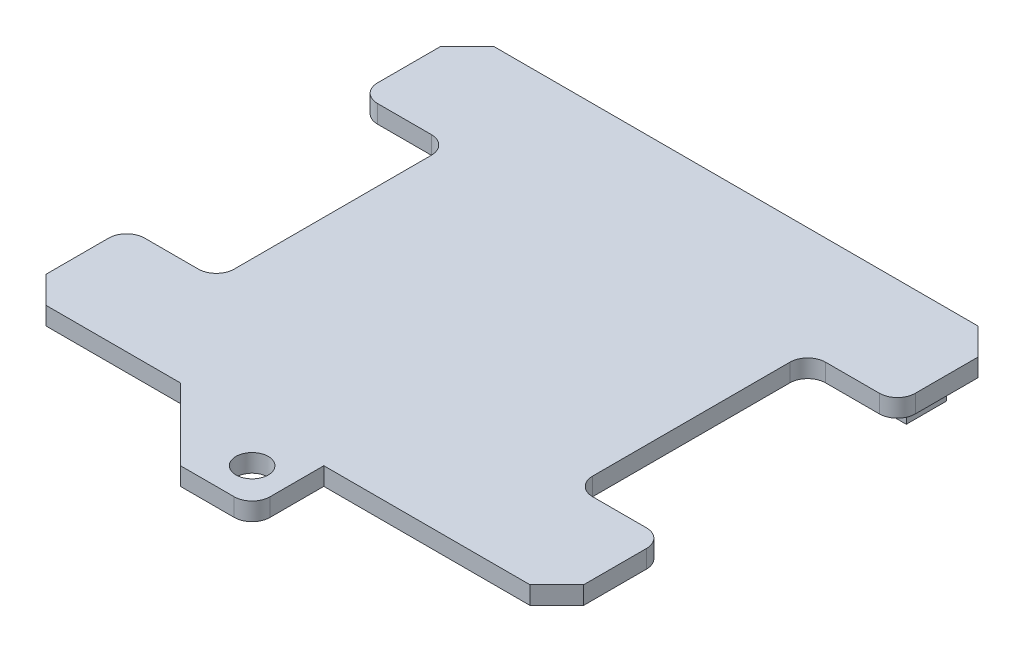
SolidWorks part; units mm, degrees
ref_plane "Front Plane" through (0, 0, 0) normal (0, 0, 1) x (1, 0, 0)
ref_plane "Top Plane" through (0, 0, 0) normal (0, 1, 0) x (1, 0, 0)
ref_plane "Right Plane" through (0, 0, 0) normal (1, 0, 0) x (0, 0, -1)
sketch "Sketch1" plane through (0, 0, 0) normal (0, 1, 0) x (1, 0, 0)
  line L1 (0, 0) -> (60, 0)
  line L2 (0, 0) -> (0, 50)
  line L3 (0, 50) -> (60, 50)
  line L4 (60, 0) -> (60, 50)
  dimension "D1" = 50
  dimension "D2" = 60
extrude "Boss-Extrude1" add sketch "Sketch1" along normal blind 2
chamfer "Chamfer1" distance 3 angle 45 4 edges at (0, 1, -50) (0, 1, 0) (60, 1, -50) (60, 1, 0)
sketch "Sketch2" plane through (0, 0, 0) normal (0, -1, 0) x (1, 0, 0)
  line L0 (2.5, -4.0355) -> (2.5, -45.9645)
  line L1 (2.5, -45.9645) -> (4.0355, -47.5)
  line L2 (4.0355, -47.5) -> (55.9645, -47.5)
  line L3 (55.9645, -47.5) -> (57.5, -45.9645)
  line L4 (57.5, -45.9645) -> (57.5, -4.0355)
  line L5 (57.5, -4.0355) -> (55.9645, -2.5)
  line L6 (55.9645, -2.5) -> (4.0355, -2.5)
  line L7 (4.0355, -2.5) -> (2.5, -4.0355)
  line L8 (0, -3) -> (0, -47)
  line L9 (0, -47) -> (3, -50)
  line L10 (3, -50) -> (57, -50)
  line L11 (57, -50) -> (60, -47)
  line L12 (60, -47) -> (60, -3)
  line L13 (60, -3) -> (57, 0)
  line L14 (57, 0) -> (3, 0)
  line L15 (3, 0) -> (0, -3)
  line L16 (0, -3) -> (0, -33.0043) construction
  line L17 (0, -47) -> (3, -50) construction
  line L18 (3, -50) -> (57, -50) construction
  line L19 (57, -50) -> (60, -47) construction
  line L20 (60, -47) -> (60, -3) construction
  line L21 (60, -3) -> (57, 0) construction
  line L22 (57, 0) -> (3, 0) construction
  line L23 (3, 0) -> (0, -3) construction
  line L24 (4.5, -4.864) -> (4.5, -45.136)
  line L25 (4.5, -45.136) -> (4.864, -45.5)
  line L26 (4.864, -45.5) -> (55.136, -45.5)
  line L27 (55.136, -45.5) -> (55.5, -45.136)
  line L28 (55.5, -45.136) -> (55.5, -4.864)
  line L29 (55.5, -4.864) -> (55.136, -4.5)
  line L30 (55.136, -4.5) -> (4.864, -4.5)
  line L31 (4.864, -4.5) -> (4.5, -4.864)
  line L32 (57.5, -41.5) -> (2.5, -41.5)
  line L33 (0, -3) -> (0, -47) construction
  dimension "D4" = 6
  dimension "D1" = 0
  dimension "D2" = 2.5
  dimension "D3" = 2
extrude "Boss-Extrude2" add sketch "Sketch2" along normal blind 3 contours L4 L32 L28 L27 L26 L25 L24 L0 L1 L2 L3
sketch "Sketch3" plane through (0, 2, 0) normal (0, 1, 0) x (1, 0, 0)
  line L56 (26, -8) -> (32, -8)
  line L57 (34, -6) -> (34, 0)
  line L58 (34, 0) -> (57, 0)
  line L59 (57, 0) -> (60, 3)
  line L60 (60, 3) -> (60, 3.8284)
  line L61 (60, 3.8284) -> (58, 3.8284)
  line L62 (58, 3.8284) -> (56.1716, 2)
  line L63 (56.1716, 2) -> (3.8284, 2)
  line L64 (3.8284, 2) -> (2, 3.8284)
  line L65 (2, 3.8284) -> (0, 3.8284)
  line L66 (0, 3.8284) -> (0, 3)
  line L67 (0, 3) -> (3, 0)
  line L68 (3, 0) -> (18, 0)
  line L69 (18, 0) -> (26, -8)
  line L70 (26, -8) -> (32, -8)
  line L71 (34, -6) -> (34, 0)
  line L72 (34, 0) -> (57, 0)
  line L73 (57, 0) -> (60, 3)
  line L74 (60, 3) -> (60, 3.8284)
  line L75 (60, 3.8284) -> (58, 3.8284)
  line L76 (58, 3.8284) -> (56.1716, 2)
  line L77 (56.1716, 2) -> (3.8284, 2)
  line L78 (3.8284, 2) -> (2, 3.8284)
  line L79 (2, 3.8284) -> (0, 3.8284)
  line L80 (0, 3.8284) -> (0, 3)
  line L81 (0, 3) -> (3, 0)
  line L82 (3, 0) -> (18, 0)
  line L84 (18, 0) -> (26, -8)
  circle A2 centre (30, -4) radius 1.8
  circle A15 centre (30, -4) radius 2 construction
  circle A16 centre (30, -4) radius 2
  arc A20 (32, -8) -> (34, -6) centre (32, -6) ccw
  arc A24 (32, -8) -> (34, -6) centre (32, -6) ccw
  dimension "D2" = 3.6
  dimension "D1" = 0
extrude "Boss-Extrude3" add sketch "Sketch3" against normal up to surface (2 mm away)
sketch "Sketch4" plane through (0, 2, 0) normal (0, 1, 0) x (1, 0, 0)
  line L0 (0, 47) -> (0, 3) construction
  line L1 (0, 38) -> (10, 38)
  line L2 (0, 38) -> (0, 12)
  line L3 (0, 12) -> (10, 12)
  line L4 (10, 38) -> (10, 12)
  line L5 (60, 3) -> (60, 47) construction
  line L6 (60, 38) -> (50, 38)
  line L7 (60, 38) -> (60, 12)
  line L8 (60, 12) -> (50, 12)
  line L9 (50, 38) -> (50, 12)
  line L10 (5, 38) -> (5, 50) construction
  line L11 (57, 50) -> (3, 50) construction
  line L12 (5, 12) -> (5, 0) construction
  line L13 (3, 0) -> (18, 0) construction
  dimension "D1" = 10
  dimension "D2" = 26
extrude "Cut-Extrude1" cut sketch "Sketch4" against normal through all
fillet "Fillet1" radius 2 8 edges at (50, 1, -12) (60, 1, -38) (60, 1, -12) (50, 1, -38) (0, 1, -12) (10, 1, -12) (10, 1, -38) (0, 1, -38)
